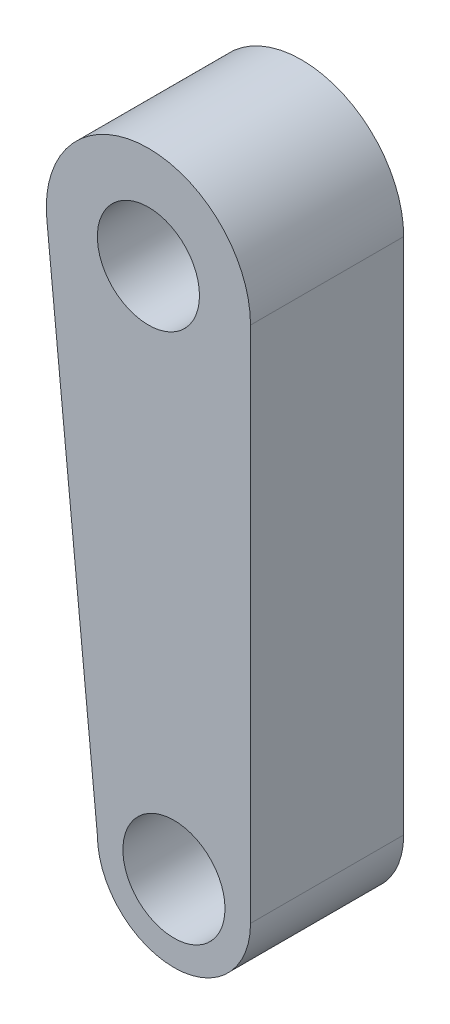
SolidWorks part; units mm, degrees
material "PUR"
ref_plane "Ön Düzlem" through (0, 0, 0) normal (0, 0, 1) x (1, 0, 0)
ref_plane "Üst Düzlem" through (0, 0, 0) normal (0, 1, 0) x (1, 0, 0)
ref_plane "Sağ Düzlem" through (0, 0, 0) normal (1, 0, 0) x (0, 0, -1)
sketch "Çizim1" plane through (0, 0, 0) normal (0, 0, 1) x (1, 0, 0)
  line L0 (-4.4853, 3.9002) -> (-3, -11.0261)
  line L1 (1.5, 4.1972) -> (1.5, -11.0261)
  arc A0 (1.5, 4.1972) -> (-4.4853, 3.9002) centre (-1.5, 4.1972) ccw
  arc A1 (-3, -11.0261) -> (1.5, -11.0261) centre (-0.75, -11.0261) ccw
  circle A2 centre (-1.5, 4.1972) radius 1.5
  circle A3 centre (-0.75, -11.0261) radius 1.5
  dimension "D1" = 6
  dimension "D3" = 3
  dimension "D4" = 2.25
  dimension "D2" = 15
extrude "Yükseklik-Ekstrüzyon1" add sketch "Çizim1" along normal blind 4.5
